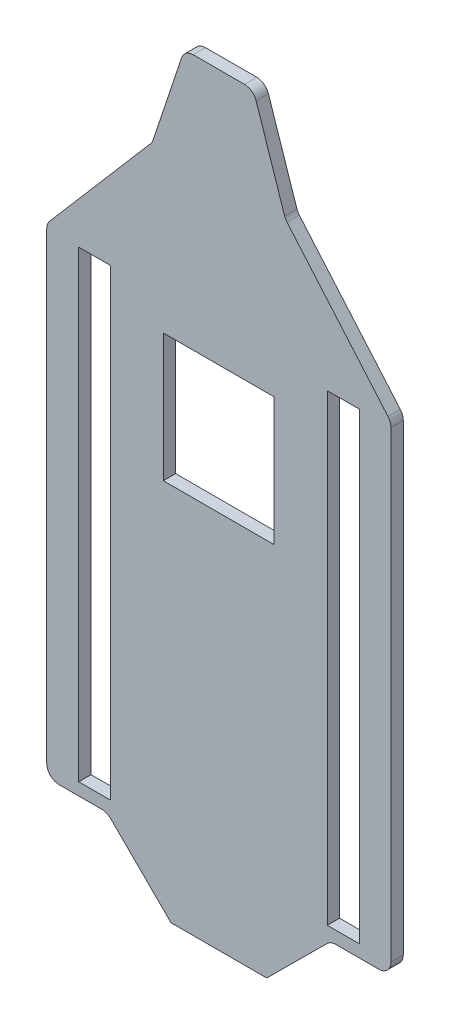
SolidWorks part; units mm, degrees
ref_plane "Front Plane" through (0, 0, 0) normal (0, 0, 1) x (1, 0, 0)
ref_plane "Top Plane" through (0, 0, 0) normal (0, 1, 0) x (1, 0, 0)
ref_plane "Right Plane" through (0, 0, 0) normal (1, 0, 0) x (0, 0, -1)
sketch "Sketch1" plane through (0, 0, 0) normal (0, 0, 1) x (1, 0, 0)
  line L0 (0, 30.8599) -> (0, 219.0089)
  line L1 (25.9628, 24.405) -> (50.5, 0)
  line L2 (59.5039, 309.9858) -> (80.3789, 309.9858)
  line L3 (134.8829, 25.8599) -> (117.446, 25.8599)
  line L5 (5, 25.8599) -> (22.4368, 25.8599)
  line L6 (96.9829, 270.8599) -> (83.9829, 270.8599) construction
  line L7 (0, 220.8599) -> (3.9, 220.8599) construction
  line L8 (3.9, 220.8599) -> (42.9, 220.8599) construction
  line L9 (42.9, 220.8599) -> (42.9, 270.8599) construction
  line L10 (96.9829, 220.8599) -> (96.9829, 270.8599) construction
  line L11 (115.3829, 25.8599) -> (89.3829, 25.8599) construction
  line L12 (24.5, 25.8599) -> (50.5, 25.8599) construction
  line L13 (0, 0) -> (0, 25.8599) construction
  line L14 (42.9, 270.8599) -> (55.9, 270.8599) construction
  line L15 (55.9, 270.8599) -> (55.9, 310) construction
  line L16 (54.8024, 306.5671) -> (43.2101, 271.7903)
  line L17 (42.2614, 270.1156) -> (1.2053, 222.2648)
  line L18 (50.5, 25.8599) -> (50.5, 0) construction
  line L20 (135.9829, 220.8599) -> (96.9829, 220.8599) construction
  line L21 (139.8829, 220.8599) -> (135.9829, 220.8599) construction
  line L22 (97.6215, 270.1156) -> (138.6775, 222.2648)
  line L23 (85.0805, 306.5671) -> (96.6727, 271.7903)
  line L24 (139.8829, 30.8599) -> (139.8829, 219.0089)
  line L25 (89.3829, 25.8599) -> (89.3829, 0) construction
  line L26 (113.92, 24.405) -> (89.3829, 0)
  line L27 (89.3829, 0) -> (50.5, 0)
  line L28 (0, 219.0089) -> (13, 219.0089) construction
  line L29 (13, 219.0089) -> (13, 30.8599)
  line L30 (13, 30.8599) -> (26, 30.8599)
  line L31 (26, 30.8599) -> (26, 219.0089)
  line L32 (26, 219.0089) -> (13, 219.0089)
  line L35 (127, 30.8599) -> (114, 30.8599)
  line L36 (114, 219.0089) -> (127, 219.0089)
  line L37 (114, 30.8599) -> (114, 219.0089)
  line L38 (127, 219.0089) -> (127, 30.8599)
  arc A0 (54.8024, 306.5671) -> (59.5039, 309.9858) centre (59.5458, 304.986) cw
  arc A1 (42.2614, 270.1156) -> (43.2101, 271.7903) centre (38.4667, 273.3715) ccw
  arc A2 (0, 219.0089) -> (1.2053, 222.2648) centre (5, 219.0089) cw
  arc A3 (85.0805, 306.5671) -> (80.3789, 309.9858) centre (80.337, 304.986) ccw
  arc A4 (139.8829, 219.0089) -> (138.6775, 222.2648) centre (134.8829, 219.0089) ccw
  arc A5 (97.6215, 270.1156) -> (96.6727, 271.7903) centre (101.4161, 273.3715) cw
  arc A6 (117.446, 25.8599) -> (113.92, 24.405) centre (117.446, 20.8599) ccw
  arc A7 (22.4368, 25.8599) -> (25.9628, 24.405) centre (22.4368, 20.8599) cw
  arc A8 (134.8829, 25.8599) -> (139.8829, 30.8599) centre (134.8829, 30.8599) ccw
  arc A9 (5, 25.8599) -> (0, 30.8599) centre (5, 30.8599) cw
  dimension "D1" = 5
  dimension "D2" = 5
  dimension "D3" = 5
extrude "Boss-Extrude1" add sketch "Sketch1" along normal blind 5
sketch "Sketch2" plane through (0, 0, 5) normal (0, 0, 1) x (1, 0, 0)
  line L2 (92.3829, 206.0089) -> (47.3829, 206.0089)
  line L3 (26, 219.0089) -> (26, 206.0089)
  line L4 (26, 30.8599) -> (26, 219.0089) construction
  line L8 (47.3829, 206.0089) -> (47.3829, 154.0089)
  line L9 (47.3829, 154.0089) -> (92.3829, 154.0089)
  line L10 (92.3829, 206.0089) -> (92.3829, 154.0089)
extrude "Cut-Extrude1" cut sketch "Sketch2" against normal through all contours L10 L2 L8 L9
